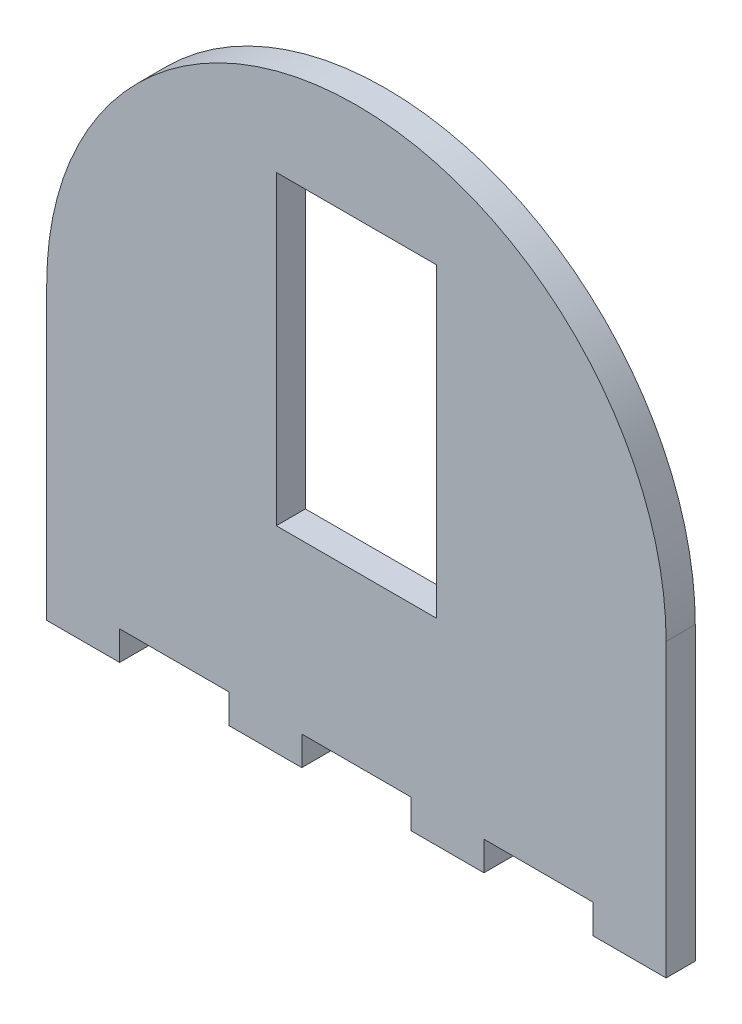
SolidWorks part; units mm, degrees
ref_plane "Alzado" through (0, 0, 0) normal (0, 0, 1) x (1, 0, 0)
ref_plane "Planta" through (0, 0, 0) normal (0, 1, 0) x (1, 0, 0)
ref_plane "Vista lateral" through (0, 0, 0) normal (1, 0, 0) x (0, 0, -1)
sketch "Croquis1" plane through (0, 0, 0) normal (0, 0, 1) x (1, 0, 0)
  line L0 (0, 0) -> (10, 0)
  line L1 (10, 0) -> (10, 4)
  line L2 (10, 4) -> (25, 4)
  line L3 (25, 4) -> (25, 0)
  line L4 (25, 0) -> (35, 0)
  line L5 (35, 0) -> (35, 4)
  line L6 (35, 4) -> (50, 4)
  line L7 (50, 4) -> (50, 0)
  line L8 (50, 0) -> (60, 0)
  line L9 (60, 0) -> (60, 4)
  line L10 (60, 4) -> (75, 4)
  line L11 (75, 4) -> (75, 0)
  line L12 (75, 0) -> (85, 0)
  line L13 (85, 0) -> (85, 40)
  line L14 (0, 0) -> (0, 40)
  line L15 (0, 40) -> (85, 40) construction
  line L16 (42.5, 40) -> (42.5, 53.8096) construction
  arc A0 (0, 40) -> (85, 40) centre (42.5, 40) cw
  dimension "D1" = 40
  dimension "D2" = 4
  dimension "D3" = 15
  dimension "D6" = 10
extrude "Saliente-Extruir1" add sketch "Croquis1" along normal blind 4
sketch "Croquis2" plane through (0, 0, 4) normal (0, 0, 1) x (1, 0, 0)
  line L0 (0, 0) -> (0, 40) construction
  line L2 (31.5, 69) -> (53.5, 69)
  line L3 (31.5, 69) -> (31.5, 27)
  line L4 (31.5, 27) -> (53.5, 27)
  line L5 (53.5, 69) -> (53.5, 27)
  circle A0 centre (42.5, 58) radius 6.5 construction
  arc A1 (85, 40) -> (0, 40) centre (42.5, 40) ccw construction
  dimension "D1" = 13
  dimension "D2" = 18
  dimension "D7" = 31
  dimension "D3" = 42.5
  dimension "D4" = 42
  dimension "D5" = 22
  dimension "D6" = 11
extrude "Cortar-Extruir1" cut sketch "Croquis2" against normal blind 4
